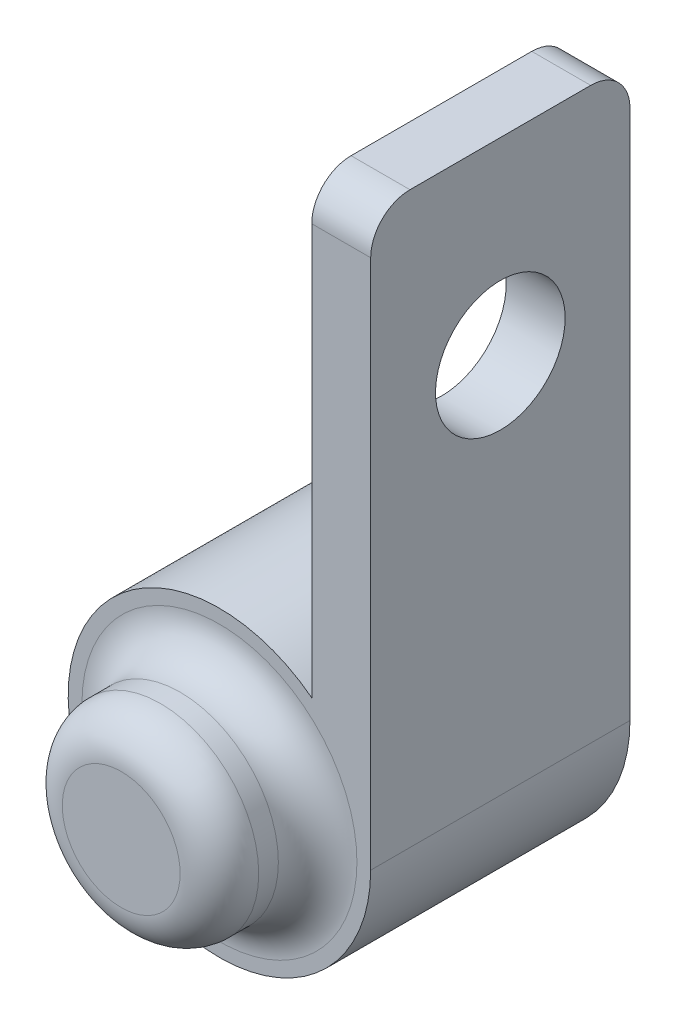
SolidWorks part; units mm, degrees
material "AISI 304"
ref_plane "前视基准面" through (0, 0, 0) normal (0, 0, 1) x (1, 0, 0)
ref_plane "上视基准面" through (0, 0, 0) normal (0, 1, 0) x (1, 0, 0)
ref_plane "右视基准面" through (0, 0, 0) normal (1, 0, 0) x (0, 0, -1)
other "Configuration Table"
sketch "草图1" plane through (0, 0, 0) normal (0, 0, 1) x (1, 0, 0)
  circle A0 centre (0, 0) radius 3.85
  dimension "D1" = 7.7
extrude "凸台-拉伸1" add sketch "草图1" along normal blind 6.6
sketch "草图2" plane through (0, 0, 6.6) normal (0, 0, 1) x (1, 0, 0)
  line L0 (3.85, 0) -> (3.85, 14.5)
  line L1 (3.85, 14.5) -> (2.35, 14.5)
  line L2 (2.35, 14.5) -> (2.35, 3.0496)
  circle A0 centre (0, 0) radius 3.85 construction
  circle A2 centre (0, 0) radius 3.85
  arc A3 (3.85, 0) -> (2.35, 3.0496) centre (0, 0) ccw
  dimension "D2" = 1.5
  dimension "D3" = 14.5
  dimension "D1" = 0
extrude "凸台-拉伸2" add sketch "草图2" against normal up to surface (6.6 mm away) up to face at (3.85, 0, 0)
sketch "草图3" plane through (0, 0, 6.6) normal (0, 0, 1) x (1, 0, 0)
  circle A0 centre (0, 0) radius 2.5
  dimension "D1" = 5
extrude "凸台-拉伸3" add sketch "草图3" along normal offset from surface (2.5 mm away) 9.1 up to face at (1.4613, 7.2064, 0)
fillet "圆角1" radius 1 2 edges at (2.5, 0, 6.6) (2.5, 0, 9.1)
sketch "草图4" plane through (2.35, 0, 0) normal (-1, 0, 0) x (0, 0, 1)
  line L0 (3.3, 14.5) -> (3.3, 9.7) construction
  line L1 (0, 14.5) -> (6.6, 14.5) construction
  circle A0 centre (3.3, 9.7) radius 1.65
  dimension "D1" = 3.3
  dimension "D2" = 9.7
extrude "切除-拉伸1" cut sketch "草图4" against normal blind 10.6
fillet "圆角2" radius 1 2 edges at (3.1, 14.5, 0) (3.1, 14.5, 6.6)
